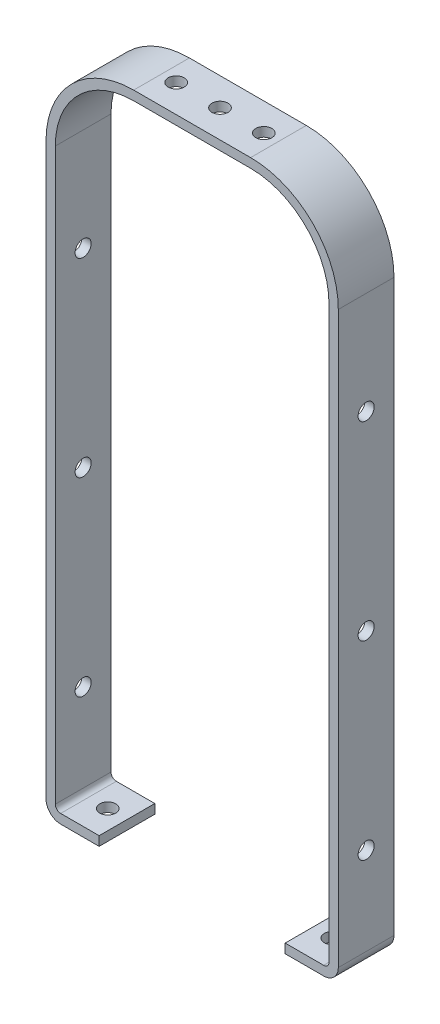
SolidWorks part; units mm, degrees
ref_plane "Front Plane" through (0, 0, 0) normal (0, 0, 1) x (1, 0, 0)
ref_plane "Top Plane" through (0, 0, 0) normal (0, 1, 0) x (1, 0, 0)
ref_plane "Right Plane" through (0, 0, 0) normal (1, 0, 0) x (0, 0, -1)
sketch "Sketch1" plane through (0, 0, 0) normal (0, 0, 1) x (1, 0, 0)
  line L0 (50, 45) -> (50, 240)
  line L1 (0, 0) -> (0, 109.6692) construction
  line L2 (46.825, 240) -> (46.825, 45)
  line L3 (-45, 40) -> (-31.825, 40)
  line L4 (20, 270) -> (-20, 270)
  line L5 (-45, 43.175) -> (-31.825, 43.175)
  line L6 (-20, 266.825) -> (20, 266.825)
  line L7 (-31.825, 43.175) -> (-31.825, 40)
  line L8 (-46.825, 240) -> (-46.825, 45)
  line L9 (-50, 45) -> (-50, 240)
  line L10 (31.825, 43.175) -> (31.825, 40)
  line L11 (45, 43.175) -> (31.825, 43.175)
  line L12 (45, 40) -> (31.825, 40)
  arc A0 (50, 240) -> (20, 270) centre (20, 240) ccw
  arc A1 (20, 266.825) -> (46.825, 240) centre (20, 240) cw
  arc A2 (-20, 266.825) -> (-46.825, 240) centre (-20, 240) ccw
  arc A3 (-50, 240) -> (-20, 270) centre (-20, 240) cw
  arc A4 (-50, 45) -> (-45, 40) centre (-45, 45) ccw
  arc A5 (-46.825, 45) -> (-45, 43.175) centre (-45, 45) ccw
  arc A6 (46.825, 45) -> (45, 43.175) centre (45, 45) cw
  arc A7 (50, 45) -> (45, 40) centre (45, 45) cw
  point P13 (0, 0)
  point P22 (0, 0)
  dimension "D4" = 30
  dimension "D5" = 45
  dimension "D6" = 3.175
  dimension "D7" = 5
  dimension "D1" = 270
  dimension "D2" = 46.825
  dimension "D3" = 40
  dimension "D8" = 15
extrude "Boss-Extrude1" add sketch "Sketch1" along normal mid plane 19.05
sketch "Sketch12" plane through (0, 270, 0) normal (0, 1, 0) x (1, 0, 0)
  line L0 (-20, -9.525) -> (-20, 9.525) construction
  line L1 (20, -9.525) -> (20, 9.525) construction
  circle A0 centre (0, 0) radius 2.75
  circle A1 centre (-15, 0) radius 2.75
  circle A2 centre (15, 0) radius 2.75
  dimension "D1" = 5.5
  dimension "D2" = 5
  dimension "D3" = 5
extrude "Cut-Extrude2" cut sketch "Sketch12" against normal through all
sketch "Sketch13" plane through (50, 0, 0) normal (1, 0, 0) x (0, 0, -1)
  line L0 (0, 0) -> (0, 240) construction
  line L1 (-9.525, 240) -> (9.525, 240) construction
  circle A0 centre (0, 205) radius 2.75
  circle A1 centre (0, 140) radius 2.75
  circle A2 centre (0, 75) radius 2.75
  dimension "D1" = 5.5
  dimension "D4" = 65
  dimension "D3" = 3
extrude "Cut-Extrude3" cut sketch "Sketch13" against normal through all both and the other way through all
sketch "Sketch16" plane through (0, 40, 0) normal (0, -1, 0) x (-1, 0, 0)
  line L0 (38.4125, -9.525) -> (38.4125, 9.525) construction
  line L1 (45, -9.525) -> (31.825, -9.525) construction
  line L2 (45, 9.525) -> (31.825, 9.525) construction
  line L3 (38.4125, 9.525) -> (31.825, 0) construction
  line L4 (31.825, -9.525) -> (31.825, 9.525) construction
  line L5 (31.825, 0) -> (45, 0) construction
  line L6 (45, -9.525) -> (45, 9.525) construction
  line L7 (0, 0) -> (0, -9.525) construction
  line L8 (20, -9.525) -> (-20, -9.525) construction
  circle A0 centre (38.4125, 0) radius 2.75
  circle A1 centre (-38.4125, 0) radius 2.75
  dimension "D1" = 5.5
extrude "Cut-Extrude6" cut sketch "Sketch16" against normal up to next
